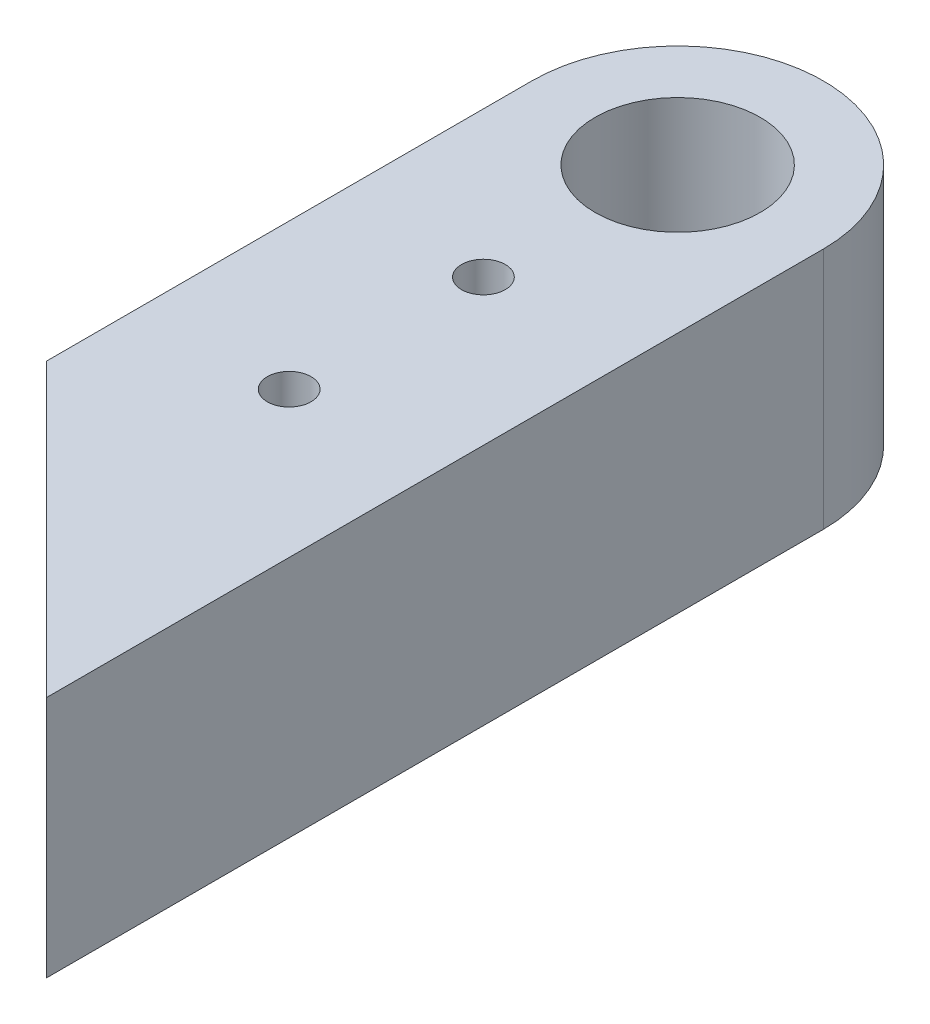
SolidWorks part; units mm, degrees
ref_plane "Front Plane" through (0, 0, 0) normal (0, 0, 1) x (1, 0, 0)
ref_plane "Top Plane" through (0, 0, 0) normal (0, 1, 0) x (1, 0, 0)
ref_plane "Right Plane" through (0, 0, 0) normal (1, 0, 0) x (0, 0, -1)
sketch "Sketch1" plane through (0, 0, 0) normal (0, 1, 0) x (1, 0, 0)
  line L0 (-15, 0) -> (-15, -50)
  line L1 (-15, -50) -> (15, -80)
  line L2 (15, -50) -> (15, 0)
  line L3 (15, -80) -> (15, -50)
  circle A0 centre (0, 0) radius 8.5
  arc A1 (15, 0) -> (-15, 0) centre (0, 0) ccw
  circle A2 centre (0, -20) radius 2.25
  circle A3 centre (0, -40) radius 2.25
  dimension "D1" = 30
  dimension "D2" = 17
  dimension "D4" = 4.5
  dimension "D3" = 50
  dimension "D5" = 20
  dimension "D6" = 20
extrude "Boss-Extrude1" add sketch "Sketch1" along normal blind 25
